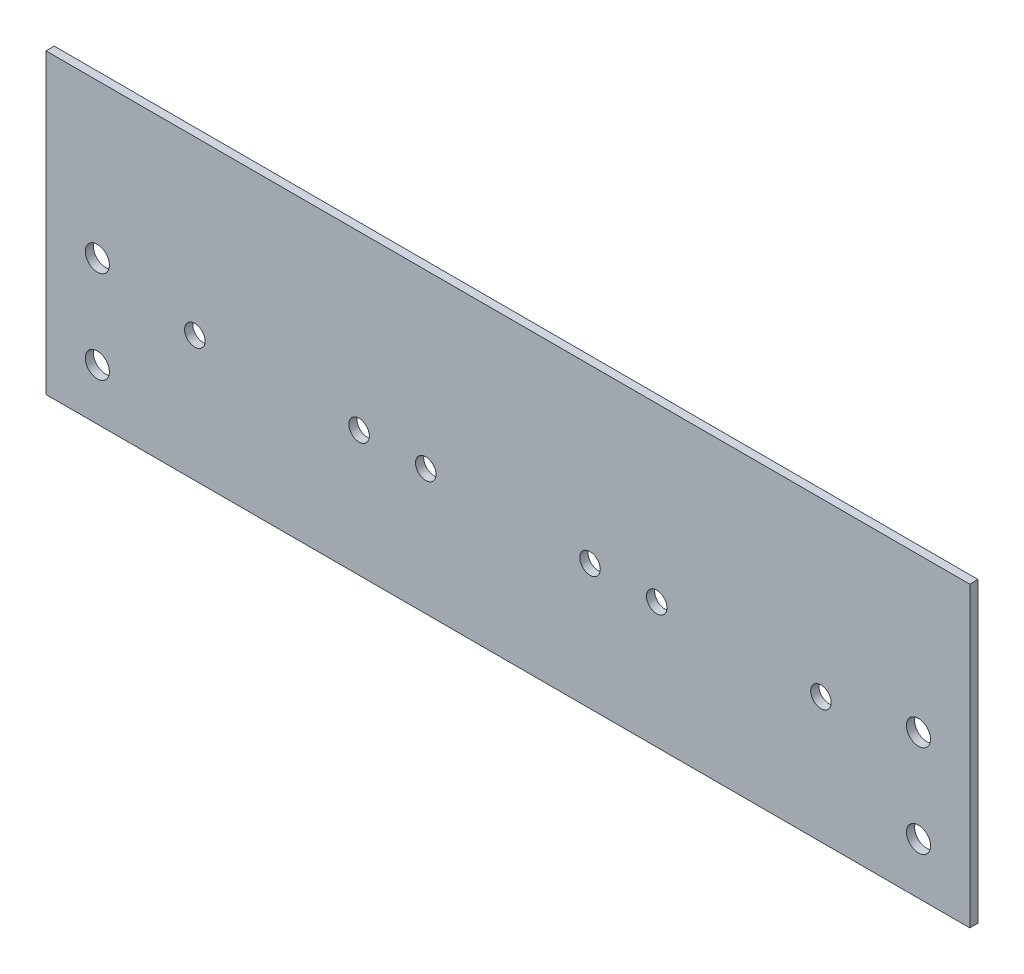
SolidWorks part; units mm, degrees
ref_plane "Front Plane" through (0, 0, 0) normal (0, 0, 1) x (1, 0, 0)
ref_plane "Top Plane" through (0, 0, 0) normal (0, 1, 0) x (1, 0, 0)
ref_plane "Right Plane" through (0, 0, 0) normal (1, 0, 0) x (0, 0, -1)
sketch "Sketch1" plane through (0, 0, 0) normal (0, 0, 1) x (1, 0, 0)
  line L2 (0, 58) -> (180, 58)
  line L3 (0, 58) -> (0, 0)
  line L4 (0, 0) -> (180, 0)
  line L5 (180, 58) -> (180, 0)
  circle A0 centre (10, 28) radius 2.35
  circle A1 centre (10, 10) radius 2.35
  circle A2 centre (29, 24.5) radius 2
  circle A3 centre (61, 24.5) radius 2
  circle A4 centre (74, 24.5) radius 2
  circle A5 centre (106, 24.5) radius 2
  circle A6 centre (119, 24.5) radius 2
  circle A7 centre (151, 24.5) radius 2
  circle A10 centre (170, 28) radius 2.35
  circle A11 centre (170, 10) radius 2.35
  point P6 (0, 0)
  point P7 (0, 0)
  point P8 (0, 0)
  point P9 (151, 24.5)
  dimension "D1" = 180
  dimension "D16" = 4
  dimension "D17" = 4.7
  dimension "D2" = 58
  dimension "D3" = 10
  dimension "D4" = 10
  dimension "D5" = 10
  dimension "D6" = 30
  dimension "D7" = 29
  dimension "D8" = 32
  dimension "D9" = 13
  dimension "D10" = 32
  dimension "D11" = 13
  dimension "D12" = 32
  dimension "D13" = 14.5
extrude "Boss-Extrude1" add sketch "Sketch1" along normal blind 1.6
